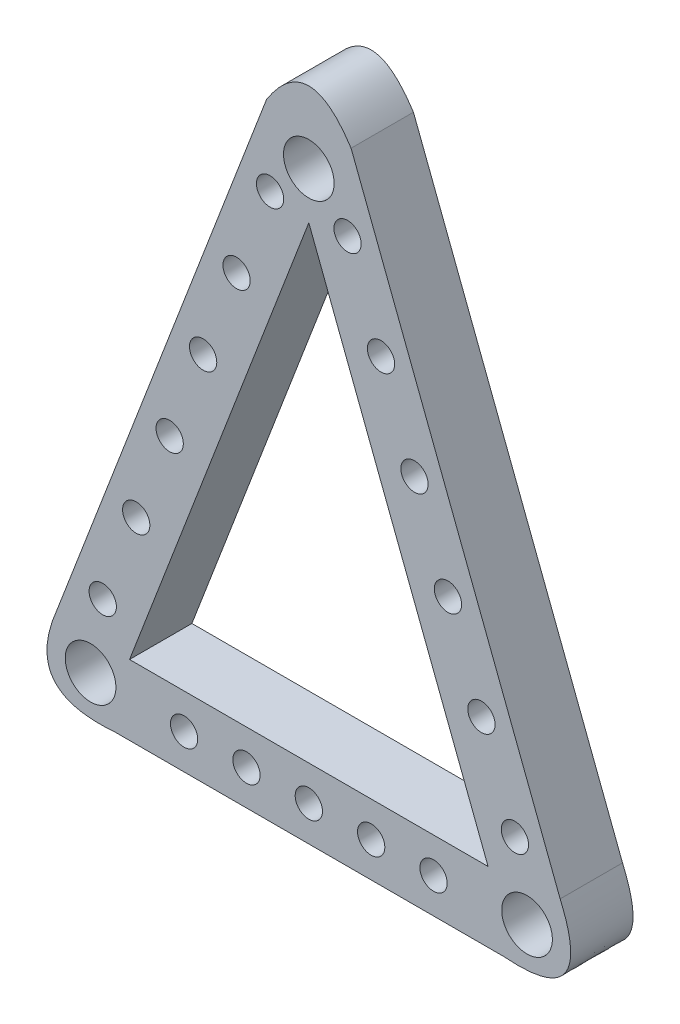
SolidWorks part; units mm, degrees
ref_plane "Front Plane" through (0, 0, 0) normal (0, 0, 1) x (1, 0, 0)
ref_plane "Top Plane" through (0, 0, 0) normal (0, 1, 0) x (1, 0, 0)
ref_plane "Right Plane" through (0, 0, 0) normal (1, 0, 0) x (0, 0, -1)
sketch "草圖1" plane through (0, 0, 0) normal (0, 0, 1) x (1, 0, 0)
  line L0 (0, 24) -> (-23, -36.0234)
  line L1 (-23, -36.0234) -> (23, -36.0234)
  line L2 (23, -36.0234) -> (0, 24)
  line L3 (-5.4231, 35) -> (-32.246, -35)
  line L4 (-25, -45.0234) -> (25, -45.0234)
  line L5 (5.4231, 35) -> (32.246, -35)
  line L6 (-5.4231, 35) -> (0, 43.4122) construction
  line L7 (0, 43.4122) -> (5.4231, 35) construction
  line L8 (32.246, -35) -> (37, -46) construction
  line L9 (37, -46) -> (25, -45.0234) construction
  line L10 (-32.246, -35) -> (-37, -46) construction
  line L11 (-37, -46) -> (-25, -45.0234) construction
  line L12 (0, 0) -> (0, 13.6547) construction
  line L13 (-4.9713, 25) -> (-26.4402, -31.0276) construction
  line L14 (-17.1776, -40.5234) -> (-7.8115, -40.5234) construction
  circle A0 centre (0, 30) radius 3.25
  circle A1 centre (-28, -40) radius 3.25
  circle A2 centre (28, -40) radius 3.25
  circle A3 centre (-4.9713, 25) radius 1.75
  circle A4 centre (-9.2651, 13.7945) radius 1.75
  circle A5 centre (-13.5589, 2.589) radius 1.75
  circle A6 centre (-17.8526, -8.6165) radius 1.75
  circle A7 centre (-22.1464, -19.8221) radius 1.75
  circle A8 centre (-26.4402, -31.0276) radius 1.75
  circle A9 centre (-16, -40.5234) radius 1.75
  circle A10 centre (-8, -40.5234) radius 1.75
  circle A11 centre (0, -40.5234) radius 1.75
  circle A13 centre (8, -40.5234) radius 1.75
  circle A14 centre (16, -40.5234) radius 1.75
  circle A15 centre (26.4402, -31.0276) radius 1.75
  circle A16 centre (22.1464, -19.8221) radius 1.75
  circle A17 centre (17.8526, -8.6165) radius 1.75
  circle A18 centre (13.5589, 2.589) radius 1.75
  circle A19 centre (9.2651, 13.7945) radius 1.75
  circle A20 centre (4.9713, 25) radius 1.75
  spline S0 degree 2 poles (-5.4231, 35) (0, 43.4122) (5.4231, 35) knots 0 0 0 1 1 1
  spline S1 degree 2 poles (32.246, -35) (37, -46) (25, -45.0234) knots 0 0 0 1 1 1
  spline S2 degree 2 poles (-32.246, -35) (-37, -46) (-25, -45.0234) knots 0 0 0 1 1 1
  point P41 (0, 0)
  dimension "D5" = 6.5
  dimension "D20" = 3.5
  dimension "D1" = 28
  dimension "D2" = 28
  dimension "D3" = 40
  dimension "D4" = 30
  dimension "D6" = 23
  dimension "D7" = 23
  dimension "D8" = 24
  dimension "D9" = 9
  dimension "D10" = 9
  dimension "D11" = 9
  dimension "D12" = 35
  dimension "D13" = 35
  dimension "D14" = 25
  dimension "D15" = 25
  dimension "D16" = 37
  dimension "D17" = 37
  dimension "D18" = 46
  dimension "D19" = 5
  dimension "D21" = 12
  dimension "D22" = 12
  dimension "D23" = 12
  dimension "D24" = 12
  dimension "D25" = 12
  dimension "D26" = 10
  dimension "D27" = 4.5
  dimension "D28" = 8
  dimension "D29" = 8
extrude "填料-伸長1" add sketch "草圖1" along normal blind 8
